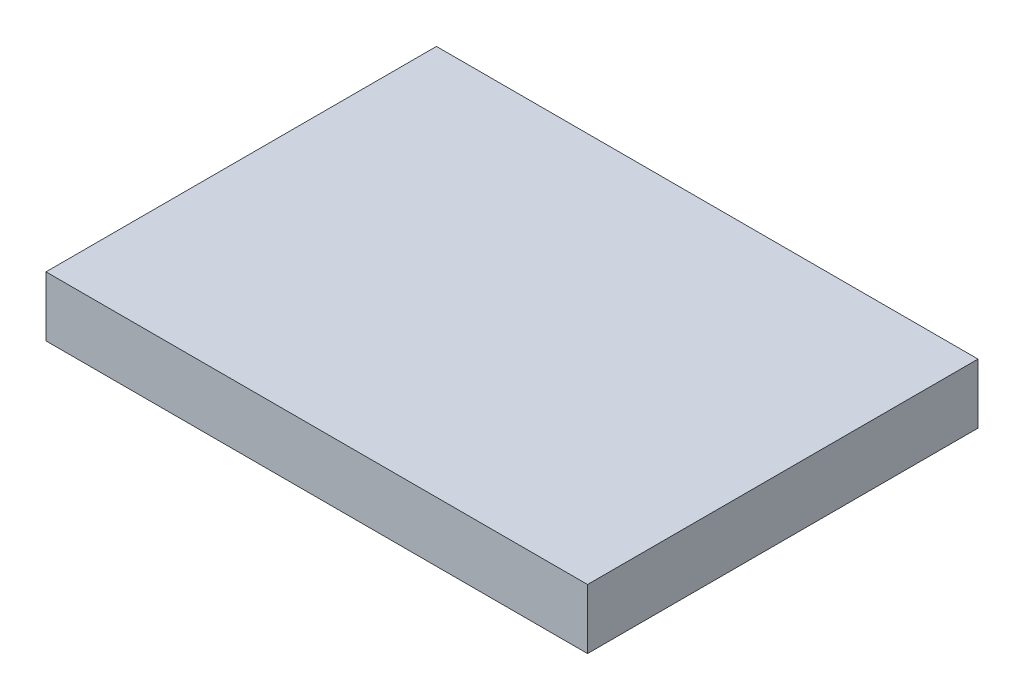
SolidWorks part; units mm, degrees
ref_plane "Plano frontal" through (0, 0, 0) normal (0, 0, 1) x (1, 0, 0)
ref_plane "Plano superior" through (0, 0, 0) normal (0, 1, 0) x (1, 0, 0)
ref_plane "Plano direito" through (0, 0, 0) normal (1, 0, 0) x (0, 0, -1)
sketch "Esboço2" plane through (0, 0, 0) normal (0, 1, 0) x (1, 0, 0)
  line L1 (-180, -130) -> (180, -130)
  line L2 (-180, -130) -> (-180, 130)
  line L3 (-180, 130) -> (180, 130)
  line L4 (180, -130) -> (180, 130)
  line L5 (-180, -130) -> (180, 130) construction
  line L6 (-180, 130) -> (180, -130) construction
  point P0 (0, 0)
  dimension "D1" = 360
  dimension "D2" = 260
extrude "Ressalto-extrusão1" add sketch "Esboço2" along normal blind 1 contours L3 L4 L1 L2
sketch "Esboço3" plane through (-180, 0, 0) normal (-1, 0, 0) x (0, 0, 1)
  line L1 (-130, 1) -> (130, 1)
  line L2 (-130, 1) -> (-130, -39)
  line L3 (-130, -39) -> (130, -39)
  line L4 (130, 1) -> (130, -39)
  dimension "D1" = 260
  dimension "D2" = 40
extrude "Ressalto-extrusão2" add sketch "Esboço3" along normal blind 1
ref_plane "Plano1" through (-180, 0, 130) normal (1, 0, 0) x (0, 0, -1)
sketch "Esboço5" plane through (0, 0, 130) normal (0, 0, 1) x (1, 0, 0)
  line L1 (180, 1) -> (-181, 1)
  line L2 (180, 1) -> (180, -39)
  line L3 (180, -39) -> (-181, -39)
  line L4 (-181, 1) -> (-181, -39)
extrude "Ressalto-extrusão3" add sketch "Esboço5" along normal blind 1
sketch "Esboço6" plane through (180, 0, 0) normal (1, 0, 0) x (0, 0, -1)
  line L1 (130, 1) -> (-131, 1)
  line L2 (130, 1) -> (130, -39)
  line L3 (130, -39) -> (-131, -39)
  line L4 (-131, 1) -> (-131, -39)
extrude "Ressalto-extrusão4" add sketch "Esboço6" along normal blind 1
